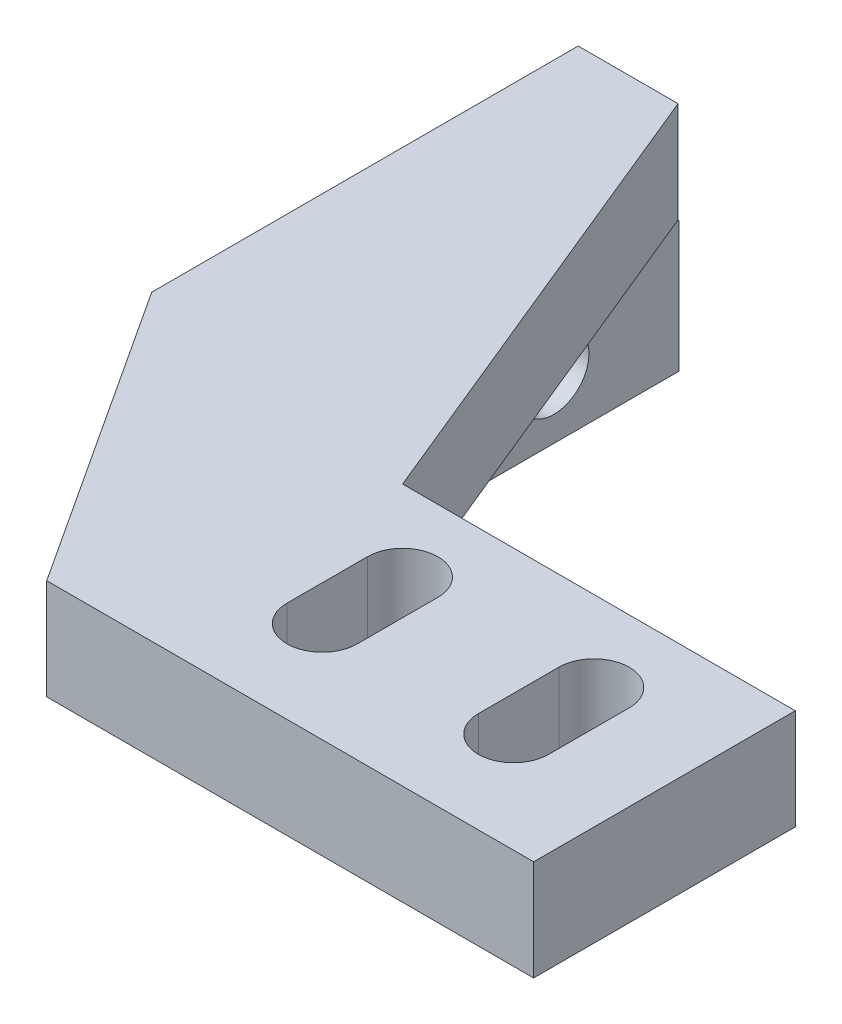
SolidWorks part; units mm, degrees
ref_plane "Piano frontale" through (0, 0, 0) normal (0, 0, 1) x (1, 0, 0)
ref_plane "Piano superiore" through (0, 0, 0) normal (0, 1, 0) x (1, 0, 0)
ref_plane "Piano destro" through (0, 0, 0) normal (1, 0, 0) x (0, 0, -1)
ref_plane "Piano1" through (0, 40, 0) normal (0, 1, 0) x (1, 0, 0)
sketch "Schizzo18" plane through (0, 40, 0) normal (0, 1, 0) x (1, 0, 0)
  line L0 (25, -16) -> (-9, -16)
  line L1 (25, -16) -> (25, -3)
  line L2 (25, -3) -> (5.4879, -3)
  line L3 (-9, 20.2124) -> (-4.0369, 20.2124)
  line L4 (-9, -16) -> (-9, 20.2124)
  line L5 (-4.0369, 20.2124) -> (5.4879, -3)
  line L6 (19, -16) -> (19, -3) construction
  line L7 (-9, -28.4145) -> (-9, 27.2974) construction
  line L8 (29.4558, -3) -> (-19.1855, -3) construction
  line L9 (25, -28.4145) -> (25, 27.2974) construction
  line L10 (29.4558, -16) -> (-19.1855, -16) construction
  line L11 (25, -11) -> (-9, -11) construction
  line L12 (25, -7) -> (-9, -7) construction
  line L13 (19, -11) -> (19, -7) construction
  line L14 (17.25, -11) -> (17.25, -7)
  line L15 (20.75, -11) -> (20.75, -7)
  line L16 (9.4906, -11) -> (9.4906, -7) construction
  line L17 (7.7406, -11) -> (7.7406, -7)
  line L18 (11.2406, -11) -> (11.2406, -7)
  arc A0 (17.25, -11) -> (20.75, -11) centre (19, -11) ccw
  arc A1 (20.75, -7) -> (17.25, -7) centre (19, -7) ccw
  arc A2 (7.7406, -11) -> (11.2406, -11) centre (9.4906, -11) ccw
  arc A3 (11.2406, -7) -> (7.7406, -7) centre (9.4906, -7) ccw
  point P22 (19, -9)
  point P29 (9.4906, -9)
  dimension "D1" = 6
  dimension "D2" = 13
  dimension "D3" = 34
  dimension "D4" = 5
  dimension "D5" = 4
extrude "Estrusione-Estrusione8" add sketch "Schizzo18" along normal blind 5 separate body
sketch "Schizzo19" plane through (0, 40, 0) normal (0, -1, 0) x (1, 0, 0)
  line L0 (-4.0369, -20.2124) -> (-9, -20.2124) construction
  line L1 (-9, 16) -> (-4, 16)
  line L2 (-9, 16) -> (-9, -20.2124)
  line L3 (-9, -20.2124) -> (-4, -20.2124)
  line L4 (-4, 16) -> (-4, -20.2124)
  dimension "D1" = 5
extrude "Estrusione-Estrusione9" add sketch "Schizzo19" along normal blind 6.5
sketch "Schizzo20" plane through (-9, 0, 0) normal (-1, 0, 0) x (0, 0, 1)
  line L0 (9, 45) -> (9, 33.5) construction
  line L1 (11, 45) -> (7, 45) construction
  line L2 (16, 33.5) -> (-20.2124, 33.5) construction
  line L3 (-9, 45) -> (-9, 33.5) construction
  line L4 (-14, 45) -> (-14, 33.5) construction
  line L13 (-4, 45) -> (-4, 33.5) construction
  line L14 (-23.6103, 33.5) -> (25.3232, 33.5) construction
  line L15 (-23.6103, 36.5) -> (25.3232, 36.5) construction
  circle A0 centre (-14, 36.5) radius 1.75
  circle A1 centre (-4, 36.5) radius 1.75
  dimension "D1" = 18
  dimension "D2" = 5
  dimension "D3" = 5
  dimension "D4" = 3
extrude "Taglio-Estrusione9" cut sketch "Schizzo20" against normal blind 6
sketch "Schizzo21" plane through (-9, 0, 0) normal (-1, 0, 0) x (0, 0, 1)
  line L0 (16, 23.2712) -> (16, 48.2769) construction
  line L1 (1, 23.2712) -> (1, 48.2769) construction
  line L2 (16, 45) -> (16, 40.1473)
  dimension "D1" = 15
sketch "Schizzo24" plane through (0, 45, 0) normal (0, 1, 0) x (1, 0, 0)
  line L0 (-9, -16) -> (25, -16) construction
  line L2 (0.8051, -16) -> (-9, -0.979)
  line L3 (-9, 20.2124) -> (-9, -16) construction
  line L4 (-9, -0.979) -> (-9, -16)
  line L5 (-9, -16) -> (0.8051, -16)
extrude "Taglio-Estrusione13" cut sketch "Schizzo24" against normal blind 21
ref_plane "Piano2" through (0, 0, 0.979) normal (0, 0, 1) x (1, 0, 0)
sketch "Schizzo26" plane through (0, 0, 0.979) normal (0, 0, 1) x (1, 0, 0)
  line L0 (-9, 23.2712) -> (-9, 48.2769) construction
  line L1 (-4, 33.5) -> (-9, 33.5)
  line L2 (-4, 33.5) -> (-4, 40)
  line L3 (-4, 40) -> (-9, 40)
  line L4 (-9, 33.5) -> (-9, 40)
  line L5 (18.7, 40) -> (-18.7, 40) construction
extrude "Taglio-Estrusione15" cut sketch "Schizzo26" along normal blind 21
